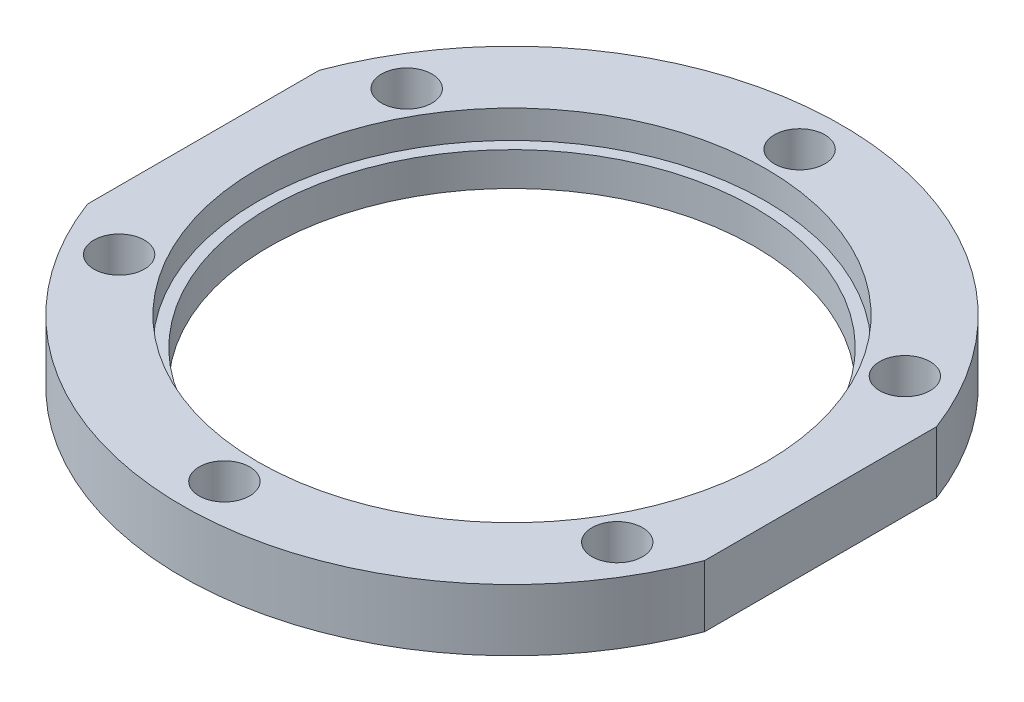
SolidWorks part; units mm, degrees
material "Сталь 20 ГОСТ 1050-88"
ref_plane "Спереди" through (0, 0, 0) normal (0, 0, 1) x (1, 0, 0)
ref_plane "Сверху" through (0, 0, 0) normal (0, 1, 0) x (1, 0, 0)
ref_plane "Справа" through (0, 0, 0) normal (1, 0, 0) x (0, 0, -1)
sketch "Эскиз1" plane through (0, 0, 0) normal (0, 0, 1) x (1, 0, 0)
  line L0 (0, 22.9348) -> (0, -71.9319) construction
  line L1 (-90.5, 0) -> (-117.5, 0)
  line L2 (-117.5, 0) -> (-117.5, -22)
  line L3 (-117.5, -22) -> (-86.5, -22)
  line L4 (-86.5, -22) -> (-86.5, -10)
  line L5 (-86.5, -10) -> (-90.5, -10)
  line L6 (-90.5, -10) -> (-90.5, 0)
  dimension "D1" = 235
  dimension "D2" = 181
  dimension "D3" = 173
  dimension "D4" = 22
  dimension "D5" = 12
revolve "Повернуть1" add sketch "Эскиз1" angle 360 about L0
sketch "Эскиз2" plane through (0, 0, 0) normal (0, 1, 0) x (1, 0, 0)
  line L0 (0, 125.4493) -> (0, -134.5901) construction
  line L1 (-110, 41.3068) -> (-110, -41.3068)
  line L2 (110, 41.3068) -> (110, -41.3068)
  circle A0 centre (0, 0) radius 117.5 construction
  arc A1 (-110, 41.3068) -> (-110, -41.3068) centre (0, 0) ccw
  arc A2 (110, -41.3068) -> (110, 41.3068) centre (0, 0) ccw
  dimension "D1" = 220
extrude "Вырез-Вытянуть1" cut sketch "Эскиз2" against normal through all
sketch "Эскиз3" plane through (0, 0, 0) normal (0, 1, 0) x (1, 0, 0)
  line L0 (0, 138.8894) -> (0, -145.9701) construction
  circle A0 centre (0, 0) radius 102.5 construction
  circle A1 centre (0, 102.5) radius 9
  point P6 (0, 102.5)
  dimension "D1" = 205
  dimension "D2" = 18
extrude "Вырез-Вытянуть2" cut sketch "Эскиз3" against normal through all
pattern_circular "Круговой массив1" count 6 over 360 about axis through (0, 0, 0) along (0, 1, 0) of "Вырез-Вытянуть2"
